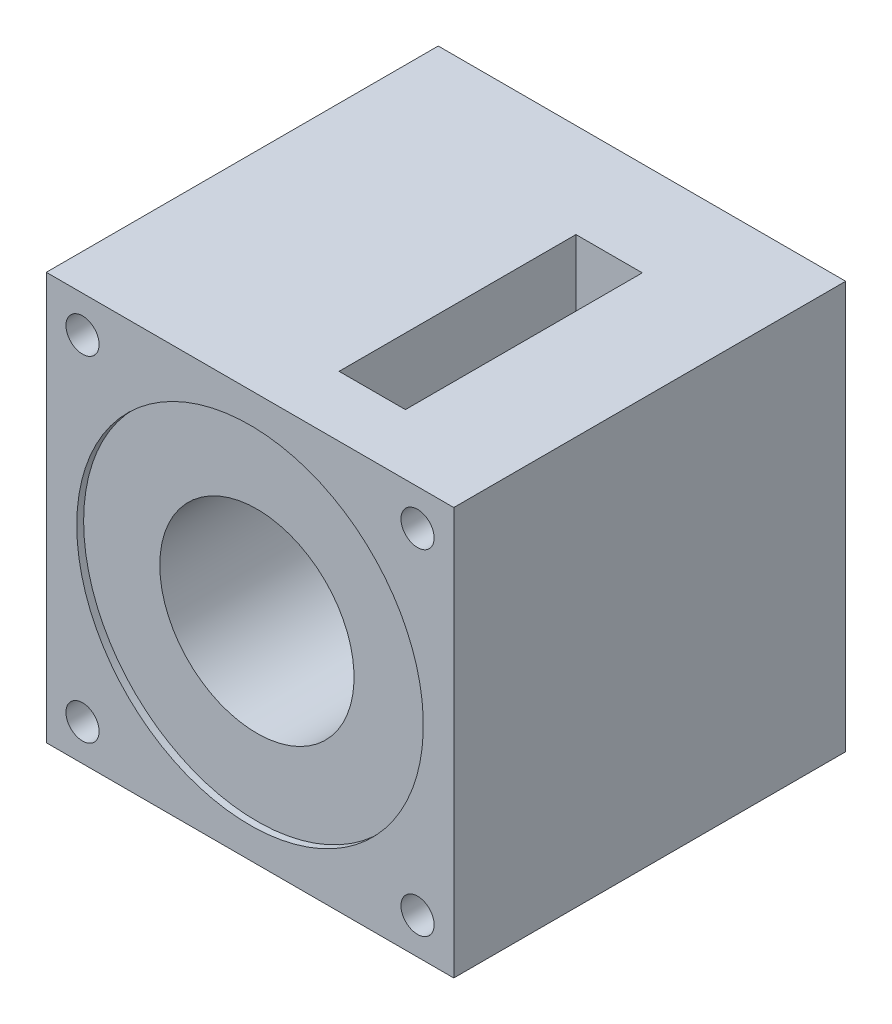
SolidWorks part; units mm, degrees
ref_plane "Front Plane" through (0, 0, 0) normal (0, 0, 1) x (1, 0, 0)
ref_plane "Top Plane" through (0, 0, 0) normal (0, 1, 0) x (1, 0, 0)
ref_plane "Right Plane" through (0, 0, 0) normal (1, 0, 0) x (0, 0, -1)
ref_plane "Plane1" through (0, 0, 0) normal (0, 0, -1) x (-1, 0, 0)
sketch "Sketch1" plane through (0, 0, 0) normal (0, 0, -1) x (-1, 0, 0)
  line L0 (361.6046, 237.5808) -> (275.6046, 237.5808)
  line L1 (275.6046, 237.5808) -> (275.6046, 151.5808)
  line L2 (275.6046, 151.5808) -> (361.6046, 151.5808)
  line L3 (361.6046, 151.5808) -> (361.6046, 237.5808)
extrude "Boss-Extrude1" add sketch "Sketch1" against normal blind 82.721
sketch "Sketch2" plane through (0, 0, 82.721) normal (0, 0, 1) x (1, 0, 0)
  circle A0 centre (-318.6046, 194.5808) radius 36.575
extrude "Cut-Extrude1" cut sketch "Sketch2" against normal blind 1.45
sketch "Sketch3" plane through (0, 0, 81.271) normal (0, 0, 1) x (1, 0, 0)
  circle A0 centre (-318.6046, 194.5808) radius 20.5
extrude "Cut-Extrude2" cut sketch "Sketch3" against normal blind 61.5
sketch "Sketch4" plane through (0, 0, 0) normal (0, 0, -1) x (-1, 0, 0)
  circle A0 centre (318.6046, 194.5808) radius 18.5
extrude "Cut-Extrude3" cut sketch "Sketch4" against normal blind 12.5
sketch "Sketch5" plane through (0, 0, 19.771) normal (0, 0, 1) x (1, 0, 0)
  circle A0 centre (-318.6046, 194.5808) radius 7.5
extrude "Cut-Extrude4" cut sketch "Sketch5" against normal through all
sketch "Sketch6" plane through (0, 237.5808, 0) normal (0, 1, 0) x (-1, 0, 0)
  line L0 (312.6046, 19.9308) -> (312.6046, 69.9308)
  line L1 (312.6046, 69.9308) -> (298.6046, 69.9308)
  line L2 (298.6046, 69.9308) -> (298.6046, 19.9308)
  line L3 (298.6046, 19.9308) -> (312.6046, 19.9308)
extrude "Cut-Extrude5" cut sketch "Sketch6" against normal up to next
hole_wizard "Ø7.0 (7) Diameter Hole1" positions "Sketch8" profile "Sketch7" hole size "Ø7.0" standard "ANSI Metric"
sketch "Sketch8" plane through (0, 0, 0) normal (0, 0, -1) x (-1, 0, 0)
  point P0 (283.6046, 159.5808)
  point P1 (283.6046, 229.5808)
  point P2 (353.6046, 159.5808)
  point P3 (353.6046, 229.5808)
sketch "Sketch7" plane through (-283.6046, 159.5808, 0) normal (1, 0, 0) x (0, 1, 0)
  line L0 (0, 0) -> (0, 22)
  line L1 (0, 22) -> (3.5, 22)
  line L2 (3.5, 22) -> (3.5, 0)
  line L5 (3.5, 0) -> (0, 0)
  line L10 (0, 22) -> (-3.5, 22) construction
  line L11 (0, -6.35) -> (0, 107.95) construction
  dimension "Hole Dia." = 7
  dimension "Hole Depth" = 22
  dimension "Drill Angle" = 180
hole_wizard "Ø7.0 (7) Diameter Hole2" positions "Sketch10" profile "Sketch9" hole size "Ø7.0" standard "ANSI Metric"
sketch "Sketch10" plane through (0, 0, 82.721) normal (0, 0, 1) x (1, 0, 0)
  point P0 (-283.2493, 159.2255)
  point P1 (-353.9599, 229.9361)
  point P2 (-283.2493, 229.9361)
  point P3 (-353.9599, 159.2255)
sketch "Sketch9" plane through (-283.2493, 159.2255, 82.721) normal (1, 0, 0) x (0, -1, 0)
  line L0 (0, 0) -> (0, 25.0002)
  line L1 (0, 25.0002) -> (3.5, 25.0002)
  line L2 (3.5, 25.0002) -> (3.5, 0)
  line L5 (3.5, 0) -> (0, 0)
  line L10 (0, 25.0002) -> (-3.5, 25.0002) construction
  line L11 (0, -6.35) -> (0, 107.95) construction
  dimension "Hole Dia." = 7
  dimension "Hole Depth" = 25.0002
  dimension "Drill Angle" = 180
